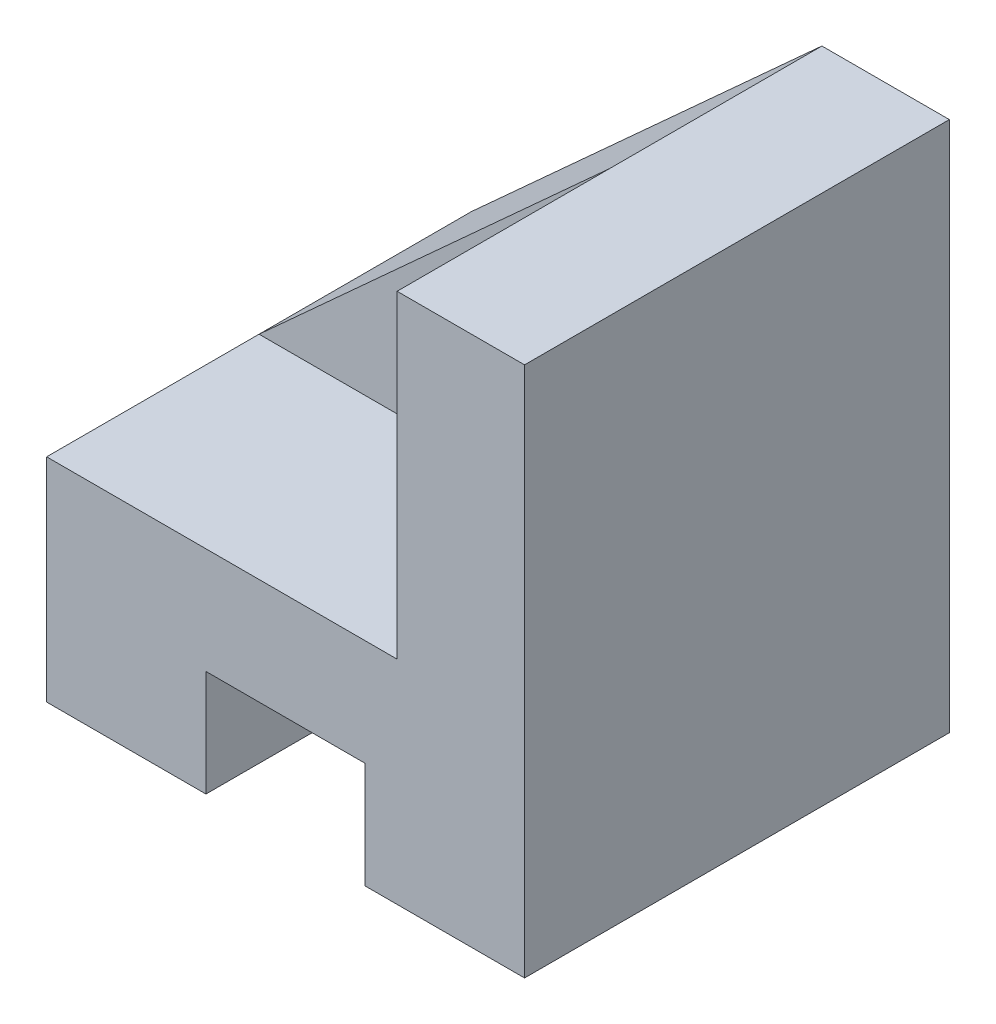
SolidWorks part; units mm, degrees
ref_plane "Front Plane" through (0, 0, 0) normal (0, 0, 1) x (1, 0, 0)
ref_plane "Top Plane" through (0, 0, 0) normal (0, 1, 0) x (1, 0, 0)
ref_plane "Right Plane" through (0, 0, 0) normal (1, 0, 0) x (0, 0, -1)
sketch "Sketch1" plane through (0, 0, 0) normal (0, 1, 0) x (1, 0, 0)
  line L1 (-22.5, -20) -> (22.5, -20)
  line L2 (-22.5, -20) -> (-22.5, 20)
  line L3 (-22.5, 20) -> (22.5, 20)
  line L4 (22.5, -20) -> (22.5, 20)
  line L5 (-22.5, -20) -> (22.5, 20) construction
  line L6 (-22.5, 20) -> (22.5, -20) construction
  point P0 (0, 0)
  dimension "D1" = 45
  dimension "D2" = 40
extrude "Boss-Extrude1" add sketch "Sketch1" along normal blind 50
sketch "Sketch2" plane through (0, 0, 20) normal (0, 0, 1) x (1, 0, 0)
  line L0 (-22.5, 0) -> (22.5, 0) construction
  line L1 (-7.5, 10) -> (7.5, 10)
  line L2 (-7.5, 10) -> (-7.5, 0)
  line L3 (-7.5, 0) -> (7.5, 0)
  line L4 (7.5, 10) -> (7.5, 0)
  dimension "D1" = 7.5
  dimension "D2" = 15
  dimension "D3" = 10
extrude "Cut-Extrude1" cut sketch "Sketch2" against normal through all
sketch "Sketch6" plane through (-22.5, 0, 0) normal (-1, 0, 0) x (0, 0, 1)
  line L0 (0, 52.8442) -> (0, -8.9052) construction
  line L1 (-25.8903, 20) -> (24.6194, 20) construction
  line L2 (0, 50) -> (0, 20)
  line L3 (-20, 50) -> (20, 50) construction
  line L4 (0, 20) -> (20, 20)
  line L5 (20, 20) -> (20, 50)
  line L6 (20, 50) -> (0, 50)
  point P11 (0, 0)
  dimension "D1" = 20
  dimension "D2" = 20
extrude "Cut-Extrude15" cut sketch "Sketch6" against normal blind 33
sketch "Sketch7" plane through (0, 0, 0) normal (0, 0, 1) x (1, 0, 0)
  line L0 (10.5, 50) -> (-22.5, 20)
extrude "Cut-Extrude16" cut sketch "Sketch7" against normal blind 20 and the other way through all flip side to cut
